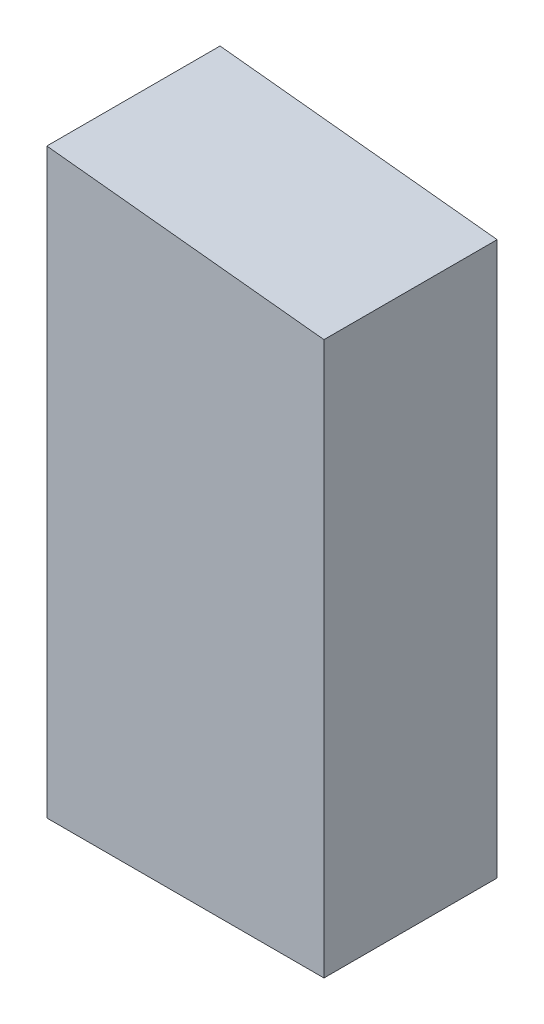
SolidWorks part; units mm, degrees
ref_plane "Plan de face" through (0, 0, 0) normal (0, 0, 1) x (1, 0, 0)
ref_plane "Plan de dessus" through (0, 0, 0) normal (0, 1, 0) x (1, 0, 0)
ref_plane "Plan de droite" through (0, 0, 0) normal (1, 0, 0) x (0, 0, -1)
sketch "Esquisse1" plane through (0, 0, 0) normal (0, 0, 1) x (1, 0, 0)
  line L1 (0, 0) -> (40, 0)
  line L2 (0, 0) -> (0, 84)
  line L3 (0, 84) -> (40, 84)
  line L4 (40, 0) -> (40, 84)
  dimension "D1" = 40
  dimension "D2" = 84
extrude "Boss.-Extru.1" add sketch "Esquisse1" along normal blind 25
sketch "Esquisse2" plane through (0, 0, 25) normal (0, 0, 1) x (1, 0, 0)
  line L0 (40, 79.7958) -> (0, 84)
  line L1 (40, 0) -> (40, 84) construction
  line L2 (0, 84) -> (40, 84)
  line L3 (40, 84) -> (40, 79.7958)
  dimension "D1" = 6
extrude "Enlèv. mat.-Extru.1" cut sketch "Esquisse2" against normal through all both and the other way through all
